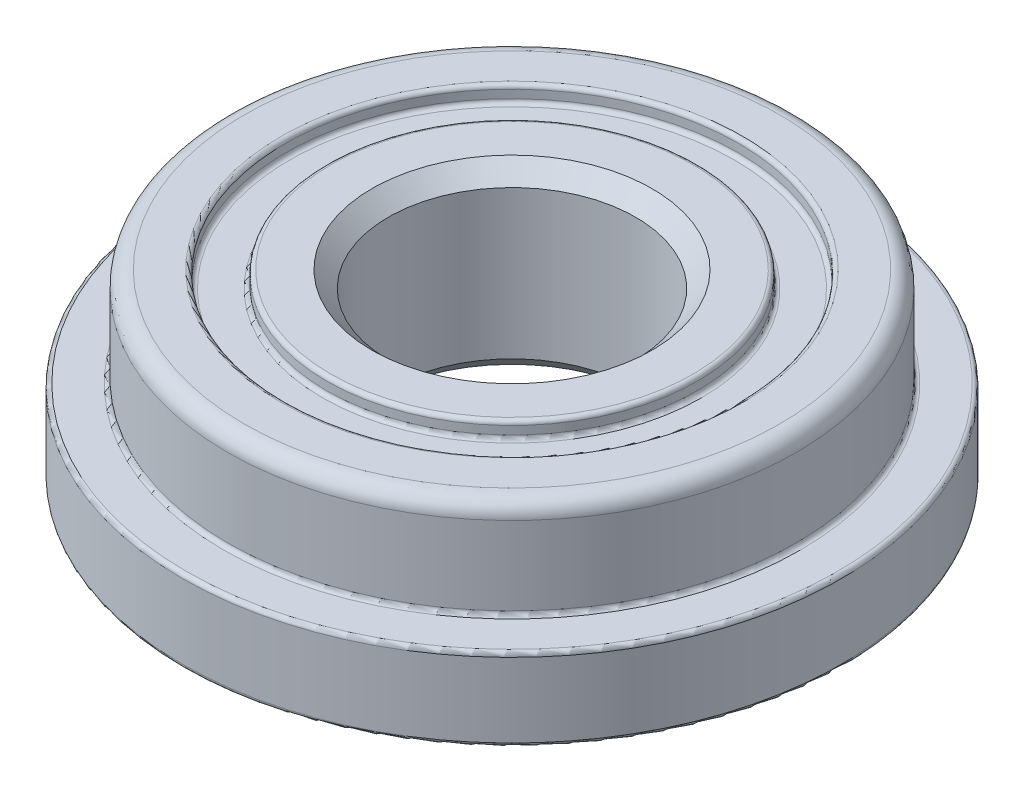
SolidWorks part; units mm, degrees
ref_plane "Front Plane" through (0, 0, 0) normal (0, 0, 1) x (1, 0, 0)
ref_plane "Top Plane" through (0, 0, 0) normal (0, 1, 0) x (1, 0, 0)
ref_plane "Right Plane" through (0, 0, 0) normal (1, 0, 0) x (0, 0, -1)
sketch "Sketch1" plane through (0, 0, 0) normal (0, 1, 0) x (1, 0, 0)
  circle A0 centre (0, 0) radius 4
  dimension "D1" = 8
extrude "Boss-Extrude1" add sketch "Sketch1" along normal blind 1
sketch "Sketch3" plane through (0, 1, 0) normal (0, 1, 0) x (1, 0, 0)
  circle A0 centre (0, 0) radius 3.45
  dimension "D1" = 6.9
extrude "Boss-Extrude2" add sketch "Sketch3" along normal blind 1.2
fillet "Fillet1" radius 0.2 1 edges at (0, 2.2, 3.45)
sketch "Sketch4" plane through (0, 2.2, 0) normal (0, 1, 0) x (1, 0, 0)
  circle A0 centre (0, 0) radius 1.5
  dimension "D1" = 3
extrude "Cut-Extrude1" cut sketch "Sketch4" against normal through all
chamfer "Chamfer1" distance 0.2 distance2 0.2 2 edges at (0, 2.2, 1.5) (0, 0, 1.5)
sketch "Sketch5" plane through (0, 2.2, 0) normal (0, 1, 0) x (1, 0, 0)
  circle A0 centre (0, 0) radius 2.75
  circle A1 centre (0, 0) radius 2.25
  dimension "D1" = 5.5
  dimension "D2" = 4.5
extrude "Cut-Extrude2" cut sketch "Sketch5" against normal blind 0.2
fillet "Fillet2" radius 0.05 4 edges at (0, 2.2, 2.25) (0, 2, 2.25) (0, 2.2, 2.75) (0, 2, 2.75)
fillet "Fillet3" radius 0.05 3 edges at (0, 1, 4) (0, 1, 3.45) (0, 0, 4)
